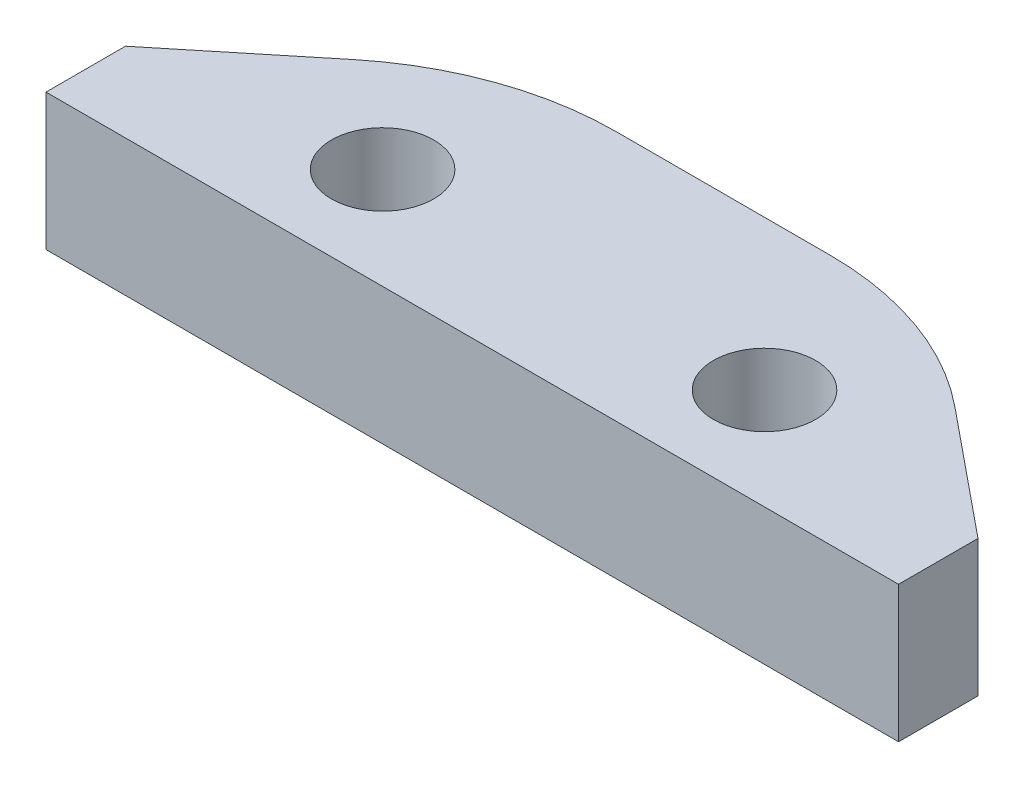
SolidWorks part; units mm, degrees
ref_plane "Alzado" through (0, 0, 0) normal (0, 0, 1) x (1, 0, 0)
ref_plane "Planta" through (0, 0, 0) normal (0, 1, 0) x (1, 0, 0)
ref_plane "Vista lateral" through (0, 0, 0) normal (1, 0, 0) x (0, 0, -1)
sketch "Croquis1" plane through (0, 0, 0) normal (0, 1, 0) x (1, 0, 0)
  line L0 (-6.341, 6.19) -> (6.341, 6.19)
  line L1 (-12.5, 1.165) -> (12.5, 1.165) construction
  line L2 (-12.5, 1.165) -> (-12.5, -1.165)
  line L3 (-12.5, -1.165) -> (12.5, -1.165)
  line L4 (12.5, 1.165) -> (12.5, -1.165)
  line L5 (-12.5, 1.165) -> (12.5, -1.165) construction
  line L6 (-12.5, -1.165) -> (12.5, 1.165) construction
  line L7 (-6.341, 6.19) -> (-12.5, 1.165)
  line L8 (6.341, 6.19) -> (12.5, 1.165)
  line L9 (0, 6.19) -> (0, -1.165) construction
  point P0 (0, 0)
  dimension "D1" = 25
  dimension "D2" = 2.33
  dimension "D3" = 129.21
extrude "Saliente-Extruir1" add sketch "Croquis1" along normal blind 4
fillet "Redondeo1" radius 9 2 edges at (6.341, 2, -6.19) (-6.341, 2, -6.19)
sketch "Croquis2" plane through (0, 4, 0) normal (0, 1, 0) x (1, 0, 0)
  line L0 (-5.6, 1.805) -> (5.6, 1.805) construction
  line L1 (0, 1.805) -> (0, -1.165) construction
  line L2 (-12.5, -1.165) -> (12.5, -1.165) construction
  circle A0 centre (-5.6, 1.805) radius 1.5
  circle A1 centre (5.6, 1.805) radius 1.5
  dimension "D1" = 3
  dimension "D2" = 11.2
  dimension "D3" = 2.97
extrude "Cortar-Extruir1" cut sketch "Croquis2" against normal through all
